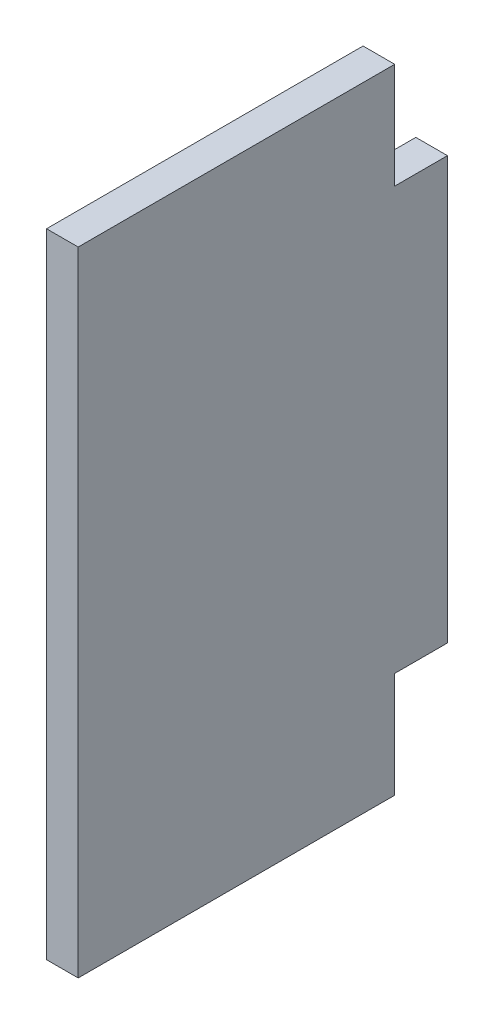
SolidWorks part; units mm, degrees
material "PVC rigido"
ref_plane "Piano frontale" through (0, 0, 0) normal (0, 0, 1) x (1, 0, 0)
ref_plane "Piano superiore" through (0, 0, 0) normal (0, 1, 0) x (1, 0, 0)
ref_plane "Piano destro" through (0, 0, 0) normal (1, 0, 0) x (0, 0, -1)
sketch "Schizzo1" plane through (0, 0, 0) normal (0, 0, 1) x (1, 0, 0)
  line L1 (89.5423, 20) -> (86.5423, 20)
  line L2 (89.5423, 20) -> (89.5423, -20)
  line L3 (89.5423, -20) -> (86.5423, -20)
  line L4 (86.5423, 20) -> (86.5423, -20)
extrude "Estrusione-Estrusione1" add sketch "Schizzo1" along normal blind 30 and the other way up to surface (5 mm away)
ref_plane "Piano1" through (0, 0, 0) normal (0, 1, 0) x (1, 0, 0)
sketch "Schizzo2" plane through (0, 20, 0) normal (0, 1, 0) x (1, 0, 0)
  line L1 (86.5423, 0) -> (89.5423, 0)
  line L2 (86.5423, 0) -> (86.5423, -30)
  line L3 (86.5423, -30) -> (89.5423, -30)
  line L4 (89.5423, 0) -> (89.5423, -30)
extrude "Estrusione-Estrusione2" add sketch "Schizzo2" along normal blind 10
mirror "Specchia1" about plane through (0, 0, 0) normal (0, 1, 0) of "Estrusione-Estrusione2"
